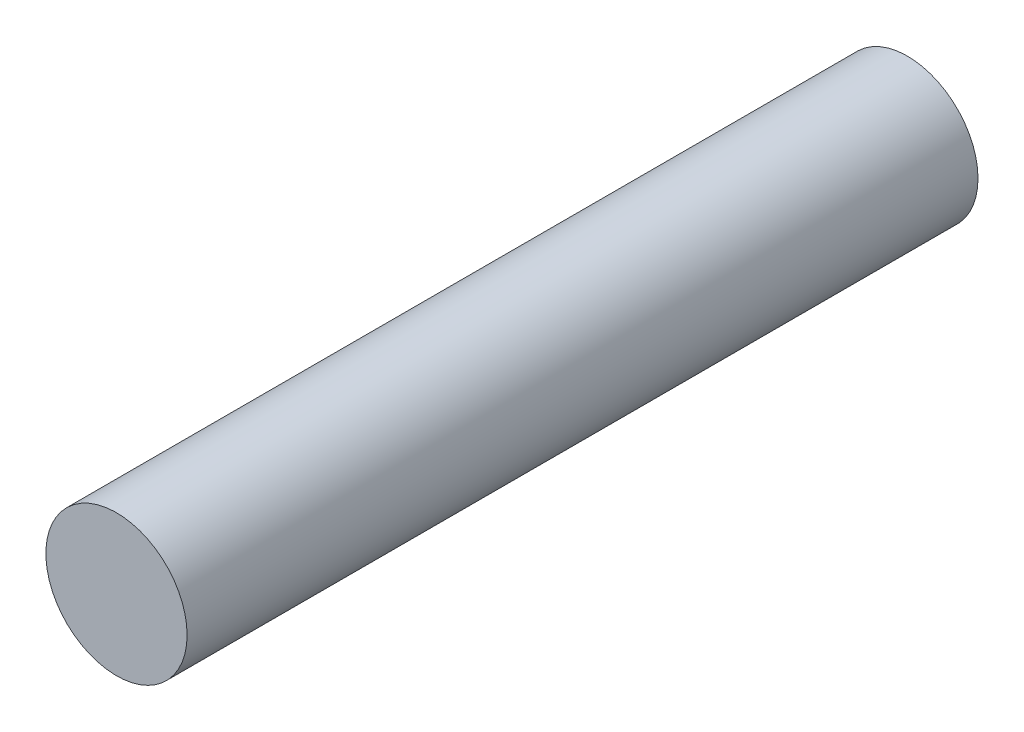
SolidWorks part; units mm, degrees
ref_plane "Frontal Plane" through (0, 0, 0) normal (0, 0, 1) x (1, 0, 0)
ref_plane "Horizontal Plane" through (0, 0, 0) normal (0, 1, 0) x (1, 0, 0)
ref_plane "Profile Plane" through (0, 0, 0) normal (1, 0, 0) x (0, 0, -1)
sketch "Sketch1" plane through (0, 0, 0) normal (0, 0, 1) x (1, 0, 0)
  circle A0 centre (0, 0) radius 3.9688
  dimension "D1" = 7.9375
extrude "Boss-Extrude1" add sketch "Sketch1" along normal blind 44.45
equation "\"BaseL\"= 6ft"
equation "\"BaseW\"= 5.5in"
equation "\"BaseThickness\"= 1in"
equation "\"RailGap\"= 4cm"
equation "\"SlidePlateL\"= 8cm"
equation "\"SlidePlateW\"= 11cm"
equation "\"SlidePlateThickness\"= 5mm"
equation "\"SlidePlateClearance\"= 1cm"
equation "\"BoxThickness\"= .5cm"
equation "\"BoxX\"= \"RailGap\" + 30mm"
equation "\"BoxH\"= 2cm + \"SlidePlateClearance\" + \"SlidePlateThickness\" + 3cm"
equation "\"BeltW\"= .375in"
equation "\"PulleyRadius\"= 15.1mm"
equation "\"PulleyH\"= 30mm + 21.4056mm - 2.5mm"
equation "\"PulleyShaftDiameter\"= .3125in"
equation "\"PulleyShaftL\"= 4in"
equation "\"MotorL\"= 4.43in"
equation "\"MotorRadius\"= 1.291in"
equation "\"MotorShaftRadius\"= .15625in"
equation "\"MotorShaftL\"= 1.75in"
equation "\"D1@Sketch1\"=\"MotorShaftRadius\"*2"
equation "\"D1@Boss-Extrude1\"=\"MotorShaftL\""
